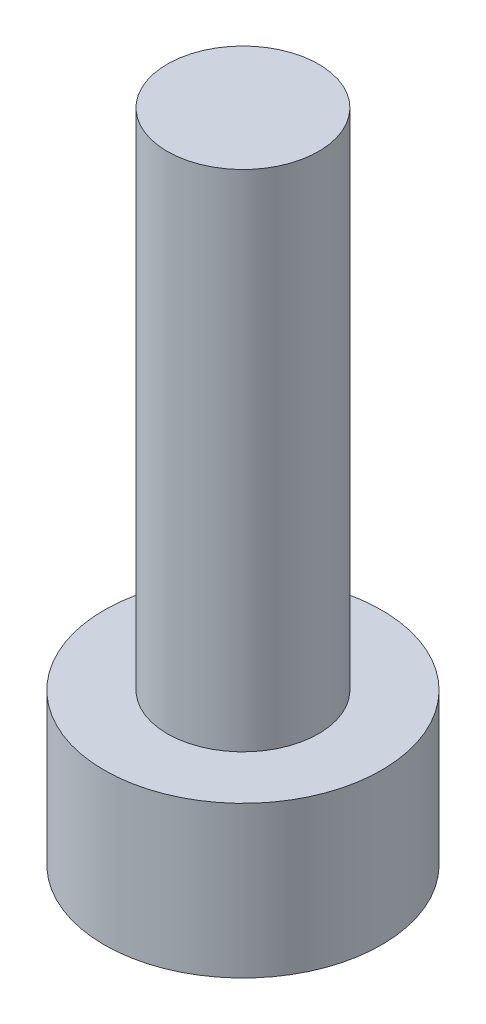
SolidWorks part; units mm, degrees
material "AISI 304"
ref_plane "前视基准面" through (0, 0, 0) normal (0, 0, 1) x (1, 0, 0)
ref_plane "上视基准面" through (0, 0, 0) normal (0, 1, 0) x (1, 0, 0)
ref_plane "右视基准面" through (0, 0, 0) normal (1, 0, 0) x (0, 0, -1)
sketch "草图1" plane through (0, 0, 0) normal (0, 0, 1) x (1, 0, 0)
  line L0 (0, 5.0793) -> (0, -4.5921) construction
  line L1 (-4.7636, 0) -> (5.5214, 0) construction
  line L2 (0, 0) -> (2.75, 0)
  line L3 (2.75, 0) -> (2.75, 3)
  line L4 (2.75, 3) -> (1.5, 3)
  line L5 (1.5, 3) -> (1.5, 13)
  line L6 (1.5, 13) -> (0, 13)
  line L7 (0, 13) -> (0, 0)
  dimension "D1" = 3
  dimension "D2" = 5.5
  dimension "D3" = 3
  dimension "D4" = 10
revolve "旋转1" add sketch "草图1" angle 360 about L0
sketch "草图2" plane through (0, 0, 0) normal (0, -1, 0) x (1, 0, 0)
  line L1 (0, -1.375) -> (1.1908, -0.6875)
  line L2 (1.1908, -0.6875) -> (1.1908, 0.6875)
  line L3 (1.1908, 0.6875) -> (0, 1.375)
  line L4 (0, 1.375) -> (-1.1908, 0.6875)
  line L5 (-1.1908, 0.6875) -> (-1.1908, -0.6875)
  line L6 (-1.1908, -0.6875) -> (0, -1.375)
  circle A0 centre (0, 0) radius 1.375 construction
  dimension "D1" = 2.75
extrude "切除-拉伸1" cut sketch "草图2" against normal blind 1.5
equation "\"长度\"= 10"
equation "\"螺钉头直径\"=5.5"
equation "\"螺钉直径\"= 3"
equation "\"螺钉头厚度\"= 3"
equation "\"D1@草图1\"= \"螺钉直径\""
equation "\"D2@草图1\"= \"螺钉头直径\""
equation "\"D3@草图1\"= \"螺钉头厚度\""
equation "\"D4@草图1\"= \"长度\""
equation "\"D1@草图2\"= \"螺钉头直径\" * 0.5"
